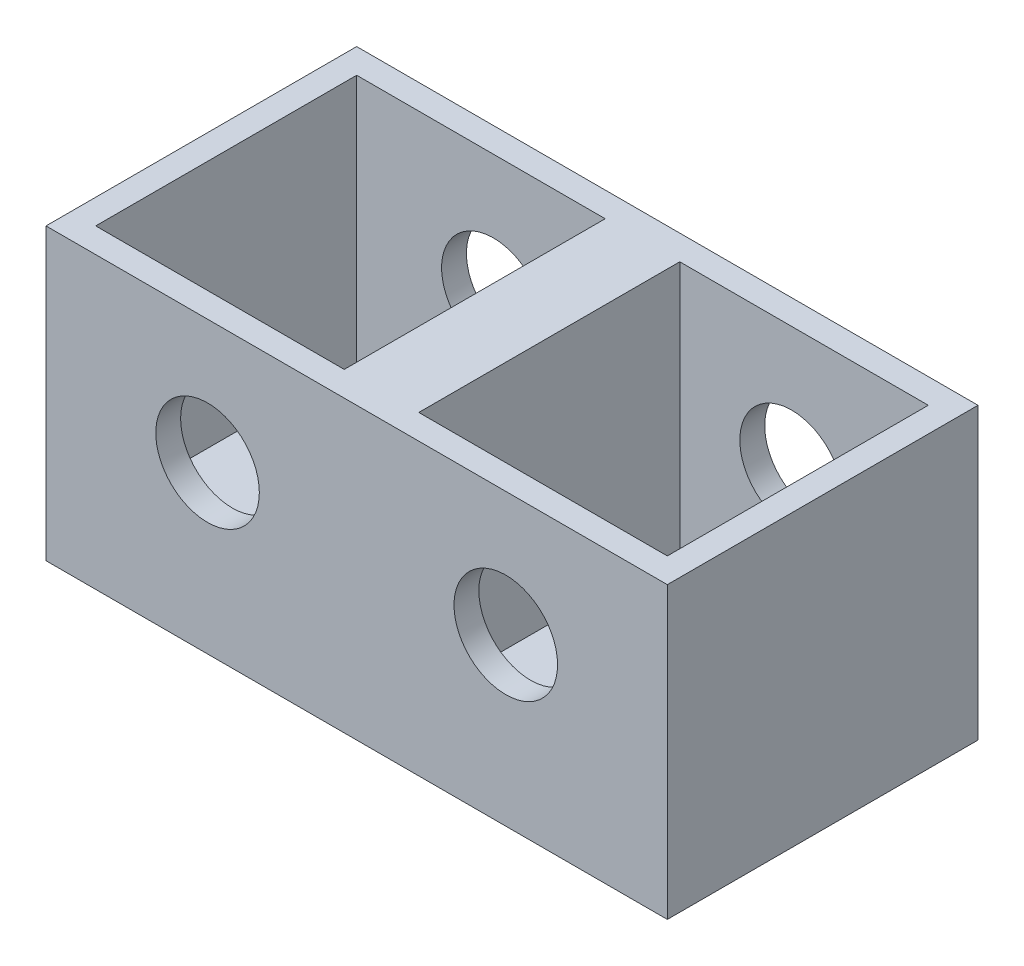
SolidWorks part; units mm, degrees
ref_plane "Front Plane" through (0, 0, 0) normal (0, 0, 1) x (1, 0, 0)
ref_plane "Top Plane" through (0, 0, 0) normal (0, 1, 0) x (1, 0, 0)
ref_plane "Right Plane" through (0, 0, 0) normal (1, 0, 0) x (0, 0, -1)
sketch "Sketch1" plane through (0, 0, 0) normal (0, 1, 0) x (1, 0, 0)
  line L1 (-15, -7.5) -> (15, -7.5)
  line L2 (-15, -7.5) -> (-15, 7.5)
  line L3 (-15, 7.5) -> (15, 7.5)
  line L4 (15, -7.5) -> (15, 7.5)
  line L5 (-15, -7.5) -> (15, 7.5) construction
  line L6 (-15, 7.5) -> (15, -7.5) construction
  point P0 (0, 0)
  dimension "D1" = 15
  dimension "D2" = 30
extrude "Boss-Extrude1" add sketch "Sketch1" along normal blind 2
sketch "Sketch2" plane through (0, 2, 0) normal (0, 1, 0) x (1, 0, 0)
  line L0 (15, 7.5) -> (-15, 7.5) construction
  line L1 (-0.6, -7.5) -> (0.6, -7.5)
  line L2 (-0.6, -7.5) -> (-0.6, 7.5)
  line L3 (-0.6, 7.5) -> (0.6, 7.5)
  line L4 (0.6, -7.5) -> (0.6, 7.5)
  line L5 (-0.6, -7.5) -> (0.6, 7.5) construction
  line L6 (-0.6, 7.5) -> (0.6, -7.5) construction
  point P0 (0, 0)
  dimension "D1" = 1.2
extrude "Boss-Extrude2" add sketch "Sketch2" along normal blind 12
sketch "Sketch3" plane through (0, 2, 0) normal (0, 1, 0) x (1, 0, 0)
  line L8 (1.8, 6.3) -> (1.8, -6.3)
  line L9 (1.8, -6.3) -> (13.8, -6.3)
  line L10 (13.8, -6.3) -> (13.8, 6.3)
  line L11 (13.8, 6.3) -> (1.8, 6.3)
  line L12 (1.8, 6.3) -> (1.8, -6.3)
  line L13 (1.8, -6.3) -> (13.8, -6.3)
  line L14 (13.8, -6.3) -> (13.8, 6.3)
  line L15 (13.8, 6.3) -> (1.8, 6.3)
  line M5 (0.6, 7.5) -> (0.6, -7.5)
  line M6 (0.6, -7.5) -> (15, -7.5)
  line M7 (15, -7.5) -> (15, 7.5)
  line M8 (15, 7.5) -> (0.6, 7.5)
  dimension "D1" = 1.2
extrude "Boss-Extrude3" add sketch "Sketch3" along normal blind 12 contours L15 L14 L13 L12 M8 M5 M6 M7
sketch "Sketch4" plane through (0, 0, 7.5) normal (0, 0, 1) x (1, 0, 0)
  line L0 (-0.6, 14) -> (-0.6, 2) construction
  line L1 (-0.6, 14) -> (15, 14) construction
  circle A0 centre (7.2, 8) radius 2.5
  point P6 (7.2, 14)
  dimension "D1" = 5
  dimension "D2" = 7.8
  dimension "D3" = 6
extrude "Cut-Extrude1" cut sketch "Sketch4" against normal blind 16
sketch "Sketch5" plane through (0, 2, 0) normal (0, 1, 0) x (1, 0, 0)
  line L8 (-1.8, -6.3) -> (-1.8, 6.3)
  line L9 (-1.8, 6.3) -> (-13.8, 6.3)
  line L10 (-13.8, 6.3) -> (-13.8, -6.3)
  line L11 (-13.8, -6.3) -> (-1.8, -6.3)
  line L12 (-1.8, -6.3) -> (-1.8, 6.3)
  line L13 (-1.8, 6.3) -> (-13.8, 6.3)
  line L14 (-13.8, 6.3) -> (-13.8, -6.3)
  line L15 (-13.8, -6.3) -> (-1.8, -6.3)
  line M5 (-0.6, -7.5) -> (-0.6, 7.5)
  line M6 (-0.6, 7.5) -> (-15, 7.5)
  line M7 (-15, 7.5) -> (-15, -7.5)
  line M8 (-15, -7.5) -> (-0.6, -7.5)
  dimension "D1" = 1.2
extrude "Boss-Extrude4" add sketch "Sketch5" along normal blind 12 contours L15 L14 L13 L12 M8 M5 M6 M7
sketch "Sketch6" plane through (0, 0, 7.5) normal (0, 0, 1) x (1, 0, 0)
  line L0 (-15, 14) -> (-15, 0) construction
  line L1 (-15, 14) -> (15, 14) construction
  circle A0 centre (-7.2, 8) radius 2.5
  dimension "D3" = 5
  dimension "D1" = 7.8
  dimension "D2" = 6
extrude "Cut-Extrude2" cut sketch "Sketch6" against normal blind 16
